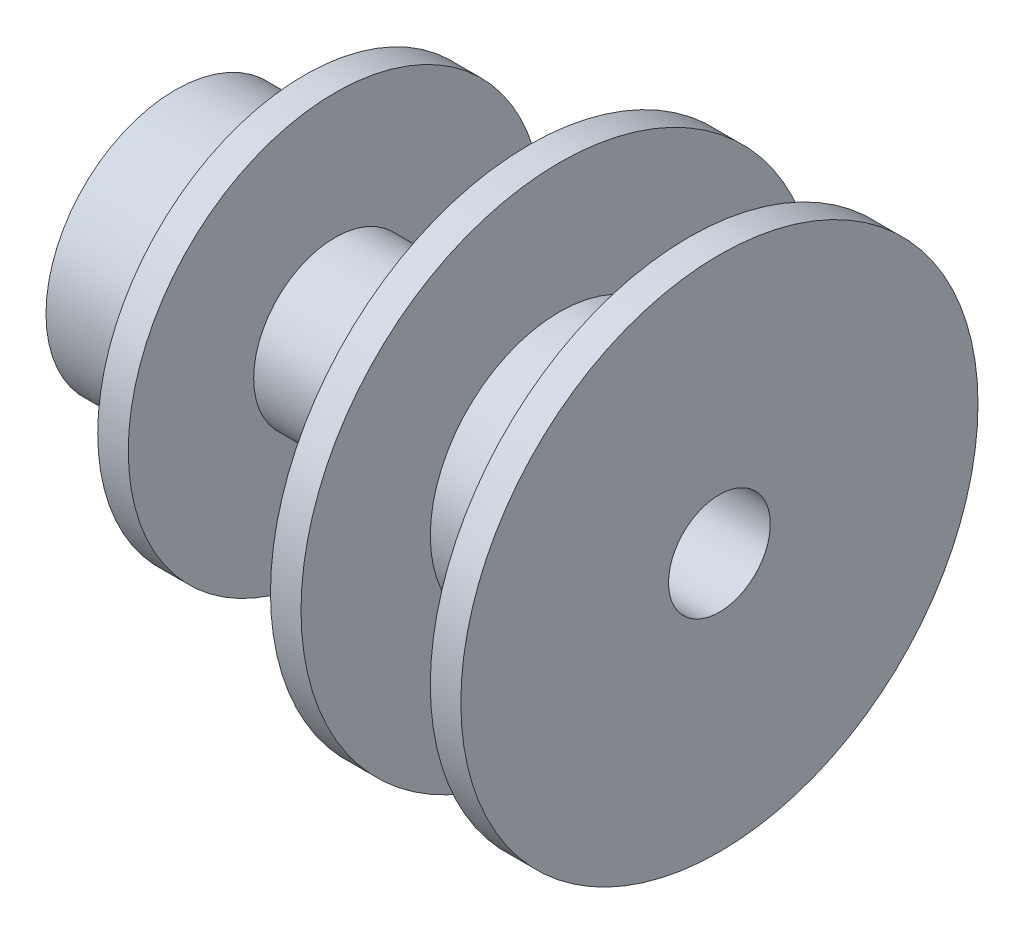
SolidWorks part; units mm, degrees
ref_plane "Front Plane" through (0, 0, 0) normal (0, 0, 1) x (1, 0, 0)
ref_plane "Top Plane" through (0, 0, 0) normal (0, 1, 0) x (1, 0, 0)
ref_plane "Right Plane" through (0, 0, 0) normal (1, 0, 0) x (0, 0, -1)
sketch "Sketch1" plane through (0, 0, 0) normal (0, 0, 1) x (1, 0, 0)
  line L0 (-93.5714, 0) -> (92.1429, 0) construction
  line L4 (-50.45, 12.7) -> (-37.75, 12.7)
  line L5 (-37.75, 12.7) -> (-37.75, 20.32)
  line L6 (-37.75, 20.32) -> (-34.75, 20.32)
  line L7 (-34.75, 20.32) -> (-34.75, 8)
  line L8 (-34.75, 8) -> (-15.7, 8)
  line L9 (-15.7, 8) -> (-15.7, 25.4)
  line L10 (-15.7, 25.4) -> (-12.7, 25.4)
  line L13 (-12.7, 25.4) -> (-12.7, 12.7)
  line L14 (-12.7, 12.7) -> (0, 12.7)
  line L15 (0, 12.7) -> (0, 25.4)
  line L16 (0, 25.4) -> (3, 25.4)
  line L17 (3, 25.4) -> (3, 5)
  line L18 (3, 5) -> (-50.45, 5)
  line L19 (-50.45, 12.7) -> (-50.45, 5)
  point P15 (1.5, 25.4)
  dimension "D2" = 20.32
  dimension "D3" = 12.7
  dimension "D5" = 5
  dimension "D6" = 12.7
  dimension "D7" = 19.05
  dimension "D8" = 3
  dimension "D10" = 3
  dimension "D11" = 3
  dimension "D12" = 12.7
  dimension "D13" = 25.4
  dimension "D14" = 25.4
  dimension "D15" = 12.7
  dimension "D16" = 7.7
revolve "Revolve1" add sketch "Sketch1" angle 360 about L0
